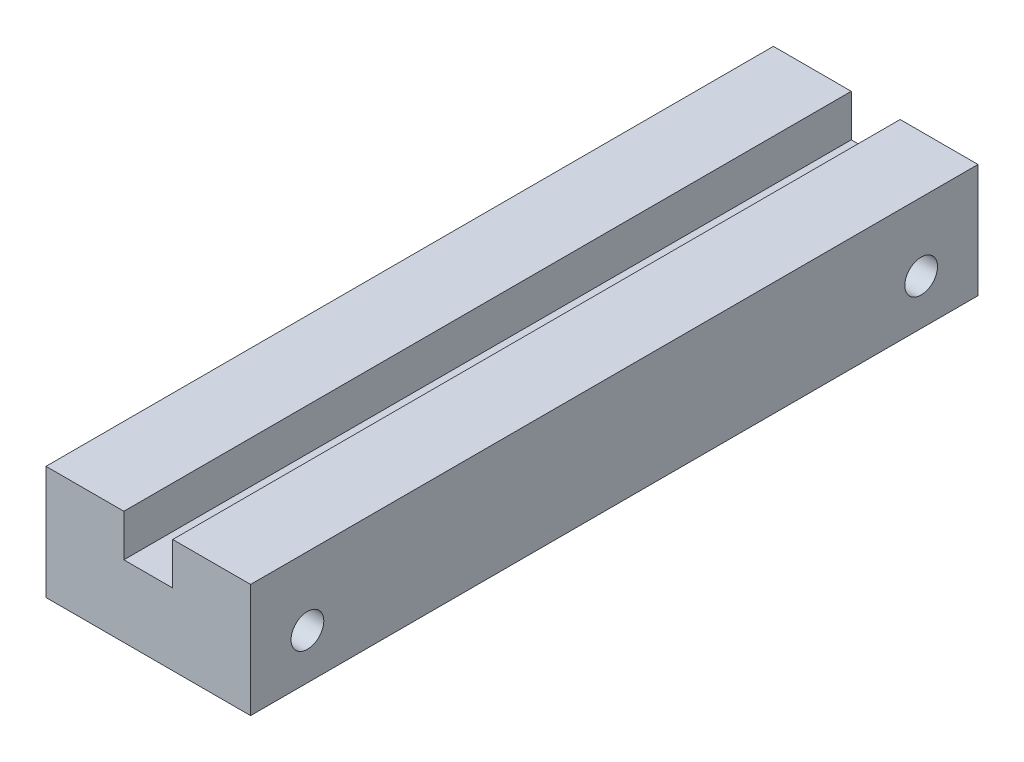
SolidWorks part; units mm, degrees
ref_plane "Front Plane" through (0, 0, 0) normal (0, 0, 1) x (1, 0, 0)
ref_plane "Top Plane" through (0, 0, 0) normal (0, 1, 0) x (1, 0, 0)
ref_plane "Right Plane" through (0, 0, 0) normal (1, 0, 0) x (0, 0, -1)
sketch "Sketch1" plane through (0, 0, 0) normal (0, 0, 1) x (1, 0, 0)
  line L1 (0, 0) -> (18, 0)
  line L2 (0, 0) -> (0, 10)
  line L3 (0, 10) -> (18, 10)
  line L4 (18, 0) -> (18, 10)
  dimension "D1" = 18
  dimension "D2" = 10
extrude "Boss-Extrude2" add sketch "Sketch1" along normal blind 64
sketch "Sketch3" plane through (0, 0, 0) normal (0, 0, -1) x (-1, 0, 0)
  line L0 (-18, 10) -> (0, 10) construction
  line L1 (-6.85, 10) -> (-11.15, 10)
  line L2 (-6.85, 10) -> (-6.85, 6.3)
  line L3 (-6.85, 6.3) -> (-11.15, 6.3)
  line L4 (-11.15, 10) -> (-11.15, 6.3)
  line L5 (-9, 10) -> (-9, 0) construction
  line L6 (0, 0) -> (-18, 0) construction
  point P10 (-9, 10)
  dimension "D1" = 4.3
  dimension "D2" = 3.7
extrude "Cut-Extrude1" cut sketch "Sketch3" against normal up to next
sketch "Sketch5" plane through (0, 6.3, 0) normal (0, 1, 0) x (1, 0, 0)
  line L0 (9, 0) -> (9, -64) construction
  line L1 (11.15, 0) -> (6.85, 0) construction
  line L2 (6.85, -64) -> (11.15, -64) construction
  line L3 (11.15, -32) -> (6.85, -32) construction
  line L4 (11.15, -64) -> (11.15, 0) construction
  line L5 (6.85, -64) -> (6.85, 0) construction
  circle A1 centre (9, -23) radius 1.425
  circle A2 centre (9, -41) radius 1.425
  circle A4 centre (9, -5) radius 1.425
  circle A5 centre (9, -59) radius 1.425
  dimension "D5" = 18
  dimension "D2" = 2.85
  dimension "D1" = 9
  dimension "D3" = 9
  dimension "D4" = 18
extrude "Cut-Extrude3" cut sketch "Sketch5" against normal blind 4.5
sketch "Sketch7" plane through (18, 0, 0) normal (1, 0, 0) x (0, 0, -1)
  line L0 (-64, 0) -> (-64, 10) construction
  line L1 (0, 0) -> (0, 10) construction
  line L2 (-64, 0) -> (0, 0) construction
  circle A0 centre (-5, 4) radius 1.4411
  circle A1 centre (-59, 4) radius 1.4411
  dimension "D1" = 5
  dimension "D2" = 5
  dimension "D3" = 4
  dimension "D4" = 4
extrude "Cut-Extrude5" cut sketch "Sketch7" against normal blind 10
sketch "Sketch8" plane through (0, 0, 0) normal (-1, 0, 0) x (0, 0, 1)
  line L0 (32, 10) -> (32, 0) construction
  line L1 (64, 10) -> (0, 10) construction
  line L2 (64, 0) -> (0, 0) construction
  circle A0 centre (23, 4) radius 1.6
  circle A1 centre (41, 4) radius 1.6
  dimension "D1" = 3.2
  dimension "D2" = 9
  dimension "D3" = 9
  dimension "D4" = 4
  dimension "D5" = 4
extrude "Cut-Extrude6" cut sketch "Sketch8" against normal blind 10
sketch "Sketch9" plane through (0, 0, 0) normal (0, 0, -1) x (-1, 0, 0)
  line L0 (0, 0) -> (-18, 0) construction
  line L1 (0, 10) -> (0, 0) construction
  circle A0 centre (-4.5, 4) radius 1.6
  dimension "D3" = 3.2
  dimension "D1" = 4
  dimension "D2" = 4.5
extrude "Cut-Extrude7" cut sketch "Sketch9" against normal blind 42.5
sketch "Sketch10" plane through (0, 0, 0) normal (0, -1, 0) x (1, 0, 0)
  line L0 (0, 32) -> (18, 32) construction
  line L1 (0, 64) -> (0, 0) construction
  line L2 (18, 64) -> (18, 0) construction
  circle A0 centre (13.5, 19.5) radius 1.25
  circle A1 centre (13.5, 44.5) radius 1.25
  dimension "D1" = 2.5
  dimension "D2" = 12.5
  dimension "D3" = 12.5
  dimension "D4" = 4.5
  dimension "D5" = 4.5
extrude "Cut-Extrude8" cut sketch "Sketch10" against normal blind 6
ref_plane "Plane1" through (0, 0, 32) normal (0, 0, -1) x (-1, 0, 0)
